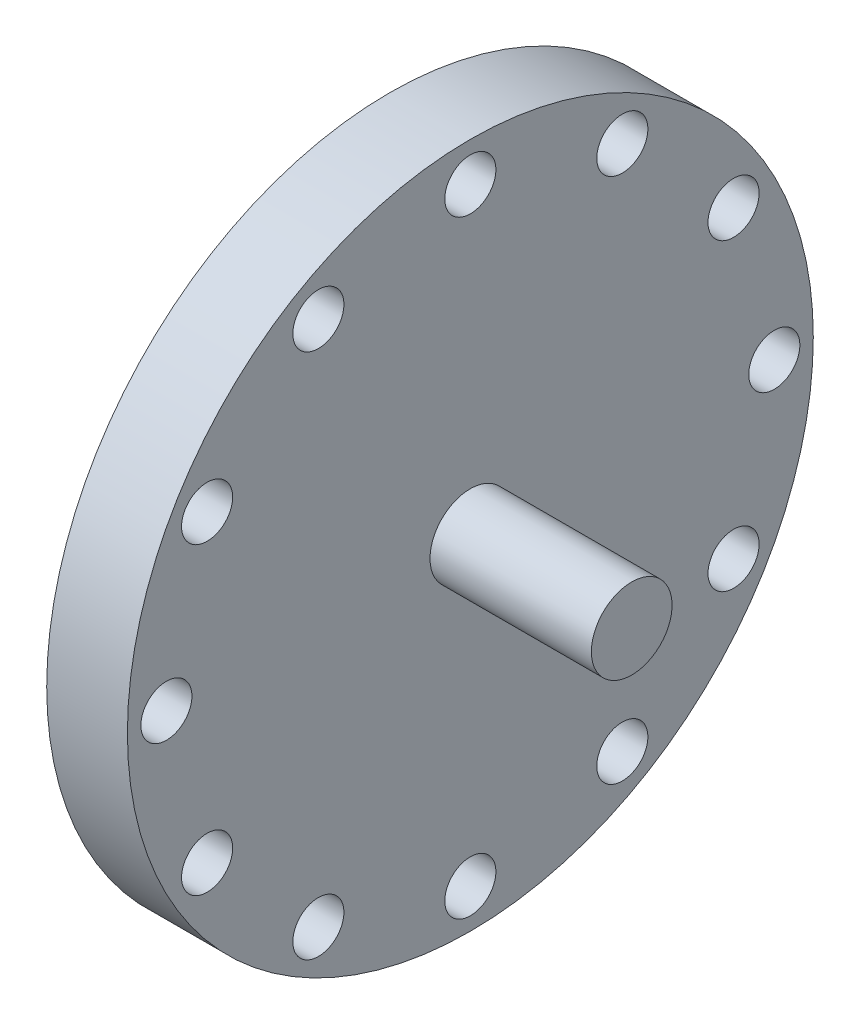
SolidWorks part; units mm, degrees
ref_plane "Спереди" through (0, 0, 0) normal (0, 0, 1) x (1, 0, 0)
ref_plane "Сверху" through (0, 0, 0) normal (0, 1, 0) x (1, 0, 0)
ref_plane "Справа" through (0, 0, 0) normal (1, 0, 0) x (0, 0, -1)
sketch "Эскиз1" plane through (0, 0, 0) normal (0, 0, 1) x (1, 0, 0)
  line L0 (0, 0) -> (100, 0)
  line L1 (0, 0) -> (0, 20)
  line L2 (0, 20) -> (10, 20)
  line L3 (10, 20) -> (10, 127.5)
  line L4 (10, 127.5) -> (40, 127.5)
  line L5 (40, 127.5) -> (40, 15)
  line L6 (40, 15) -> (100, 15)
  line L7 (100, 0) -> (100, 15)
revolve "Повернуть1" add sketch "Эскиз1" angle 360 about L0
sketch "Эскиз2" plane through (0, 0, 0) normal (1, 0, 0) x (0, 0, -1)
  circle A0 centre (0, 113) radius 9.5
extrude "Вырез-Вытянуть1" cut sketch "Эскиз2" along normal through all
sketch "Эскиз3" plane through (0, 0, 0) normal (1, 0, 0) x (0, 0, -1)
  circle A0 centre (-56.5, 97.8609) radius 9.5
extrude "Вырез-Вытянуть2" cut sketch "Эскиз3" along normal through all
sketch "Эскиз4" plane through (0, 0, 0) normal (1, 0, 0) x (0, 0, -1)
  circle A0 centre (-97.8609, 56.5) radius 9.5
extrude "Вырез-Вытянуть3" cut sketch "Эскиз4" along normal through all
sketch "Эскиз5" plane through (0, 0, 0) normal (1, 0, 0) x (0, 0, -1)
  circle A0 centre (-113, 0) radius 9.5
extrude "Вырез-Вытянуть4" cut sketch "Эскиз5" along normal through all
sketch "Эскиз6" plane through (0, 0, 0) normal (1, 0, 0) x (0, 0, -1)
  circle A0 centre (-97.8609, -56.5) radius 9.5
extrude "Вырез-Вытянуть5" cut sketch "Эскиз6" along normal through all
sketch "Эскиз7" plane through (0, 0, 0) normal (1, 0, 0) x (0, 0, -1)
  circle A0 centre (-56.5, -97.8609) radius 9.5
extrude "Вырез-Вытянуть6" cut sketch "Эскиз7" along normal through all
sketch "Эскиз8" plane through (0, 0, 0) normal (1, 0, 0) x (0, 0, -1)
  circle A0 centre (0, -113) radius 9.5
extrude "Вырез-Вытянуть7" cut sketch "Эскиз8" along normal through all
sketch "Эскиз9" plane through (0, 0, 0) normal (1, 0, 0) x (0, 0, -1)
  circle A0 centre (56.5, -97.8609) radius 9.5
extrude "Вырез-Вытянуть8" cut sketch "Эскиз9" along normal through all
sketch "Эскиз10" plane through (0, 0, 0) normal (1, 0, 0) x (0, 0, -1)
  circle A0 centre (97.8609, -56.5) radius 9.5
extrude "Вырез-Вытянуть9" cut sketch "Эскиз10" along normal through all
sketch "Эскиз11" plane through (0, 0, 0) normal (1, 0, 0) x (0, 0, -1)
  circle A0 centre (113, 0) radius 9.5
extrude "Вырез-Вытянуть10" cut sketch "Эскиз11" along normal through all
sketch "Эскиз12" plane through (0, 0, 0) normal (1, 0, 0) x (0, 0, -1)
  circle A0 centre (97.8609, 56.5) radius 9.5
extrude "Вырез-Вытянуть11" cut sketch "Эскиз12" along normal through all
sketch "Эскиз13" plane through (0, 0, 0) normal (1, 0, 0) x (0, 0, -1)
  circle A0 centre (56.5, 97.8609) radius 9.5
extrude "Вырез-Вытянуть12" cut sketch "Эскиз13" along normal through all
